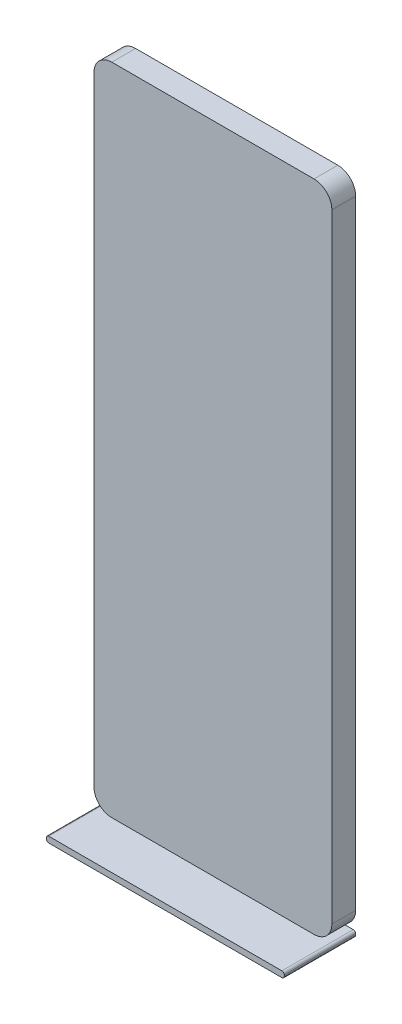
SolidWorks part; units mm, degrees
ref_plane "前视基准面" through (0, 0, 0) normal (0, 0, 1) x (1, 0, 0)
ref_plane "上视基准面" through (0, 0, 0) normal (0, 1, 0) x (1, 0, 0)
ref_plane "右视基准面" through (0, 0, 0) normal (1, 0, 0) x (0, 0, -1)
other "Configuration Table"
sketch "草图3" plane through (0, 0, 0) normal (0, 0, 1) x (1, 0, 0)
  line L0 (-17, -55) -> (17, -55)
  line L1 (20, -52) -> (20, 52)
  line L2 (17, 55) -> (-17, 55)
  line L3 (-20, 52) -> (-20, -52)
  arc A0 (17, -55) -> (20, -52) centre (17, -52) ccw
  arc A1 (20, 52) -> (17, 55) centre (17, 52) ccw
  arc A2 (-17, 55) -> (-20, 52) centre (-17, 52) ccw
  arc A3 (-20, -52) -> (-17, -55) centre (-17, -52) ccw
extrude "四毫米电池防滑垫" add sketch "草图3" along normal blind 4
sketch "草图4" plane through (0, 0, 0) normal (0, 0, 1) x (1, 0, 0)
  line L32 (-16.75, -32.25) -> (-13.75, -32.25)
  line L33 (-11.75, -30.25) -> (-11.75, -24.25)
  line L34 (-13.75, -22.25) -> (-16.75, -22.25)
  line L35 (-18.75, -24.25) -> (-18.75, -30.25)
  line L36 (-16.75, -1.75) -> (-13.75, -1.75)
  line L37 (-11.75, 0.25) -> (-11.75, 6.25)
  line L38 (-13.75, 8.25) -> (-16.75, 8.25)
  line L39 (-18.75, 6.25) -> (-18.75, 0.25)
  line L40 (13.75, -32.25) -> (16.75, -32.25)
  line L41 (18.75, -30.25) -> (18.75, -24.25)
  line L42 (16.75, -22.25) -> (13.75, -22.25)
  line L43 (11.75, -24.25) -> (11.75, -30.25)
  line L44 (13.75, -1.75) -> (16.75, -1.75)
  line L45 (18.75, 0.25) -> (18.75, 6.25)
  line L46 (16.75, 8.25) -> (13.75, 8.25)
  line L47 (11.75, 6.25) -> (11.75, 0.25)
  arc A32 (-13.75, -32.25) -> (-11.75, -30.25) centre (-13.75, -30.25) ccw
  arc A33 (-11.75, -24.25) -> (-13.75, -22.25) centre (-13.75, -24.25) ccw
  arc A34 (-16.75, -22.25) -> (-18.75, -24.25) centre (-16.75, -24.25) ccw
  arc A35 (-18.75, -30.25) -> (-16.75, -32.25) centre (-16.75, -30.25) ccw
  arc A36 (-13.75, -1.75) -> (-11.75, 0.25) centre (-13.75, 0.25) ccw
  arc A37 (-11.75, 6.25) -> (-13.75, 8.25) centre (-13.75, 6.25) ccw
  arc A38 (-16.75, 8.25) -> (-18.75, 6.25) centre (-16.75, 6.25) ccw
  arc A39 (-18.75, 0.25) -> (-16.75, -1.75) centre (-16.75, 0.25) ccw
  arc A40 (16.75, -32.25) -> (18.75, -30.25) centre (16.75, -30.25) ccw
  arc A41 (18.75, -24.25) -> (16.75, -22.25) centre (16.75, -24.25) ccw
  arc A42 (13.75, -22.25) -> (11.75, -24.25) centre (13.75, -24.25) ccw
  arc A43 (11.75, -30.25) -> (13.75, -32.25) centre (13.75, -30.25) ccw
  arc A44 (16.75, -1.75) -> (18.75, 0.25) centre (16.75, 0.25) ccw
  arc A45 (18.75, 6.25) -> (16.75, 8.25) centre (16.75, 6.25) ccw
  arc A46 (13.75, 8.25) -> (11.75, 6.25) centre (13.75, 6.25) ccw
  arc A47 (11.75, 0.25) -> (13.75, -1.75) centre (13.75, 0.25) ccw
extrude "贴顶飞控螺钉底部避让槽" cut sketch "草图4" along normal blind 3
sketch "草图5" plane through (0, 0, 0) normal (0, 0, 1) x (1, 0, 0)
  line L0 (-19.6, -56) -> (19.6, -56)
  line L1 (20, -55.6) -> (20, -55.4)
  line L2 (19.6, -55) -> (-19.6, -55)
  line L3 (-20, -55.4) -> (-20, -55.6)
  arc A0 (19.6, -56) -> (20, -55.6) centre (19.6, -55.6) ccw
  arc A1 (20, -55.4) -> (19.6, -55) centre (19.6, -55.4) ccw
  arc A2 (-19.6, -55) -> (-20, -55.4) centre (-19.6, -55.4) ccw
  arc A3 (-20, -55.6) -> (-19.6, -56) centre (-19.6, -55.6) ccw
extrude "电池仓前端一毫米缓冲唇" add sketch "草图5" along normal blind 12
